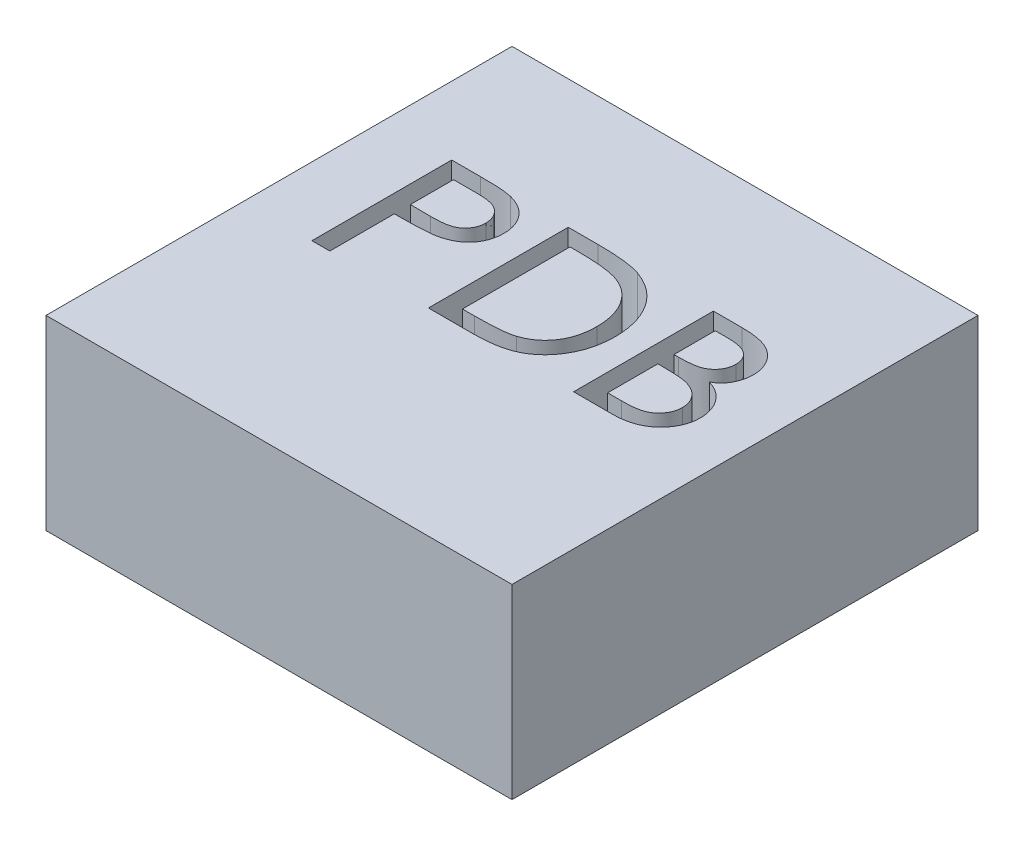
SolidWorks part; units mm, degrees
ref_plane "Front Plane" through (0, 0, 0) normal (0, 0, 1) x (1, 0, 0)
ref_plane "Top Plane" through (0, 0, 0) normal (0, 1, 0) x (1, 0, 0)
ref_plane "Right Plane" through (0, 0, 0) normal (1, 0, 0) x (0, 0, -1)
sketch "Sketch1" plane through (0, 0, 0) normal (0, 1, 0) x (1, 0, 0)
  line L1 (-31.75, -31.75) -> (31.75, -31.75)
  line L2 (-31.75, -31.75) -> (-31.75, 31.75)
  line L3 (-31.75, 31.75) -> (31.75, 31.75)
  line L4 (31.75, -31.75) -> (31.75, 31.75)
  line L5 (-31.75, -31.75) -> (31.75, 31.75) construction
  line L6 (-31.75, 31.75) -> (31.75, -31.75) construction
  point P0 (0, 0)
  dimension "D1" = 63.5
  dimension "D2" = 63.5
extrude "Boss-Extrude1" add sketch "Sketch1" along normal blind 25.4
sketch "Sketch2" plane through (0, 25.4, 0) normal (0, 1, 0) x (1, 0, 0)
  text T0 "<b>PDB</b>" font "Century Gothic" height in points 72
extrude "Cut-Extrude1" cut sketch "Sketch2" against normal mid plane 25.4
